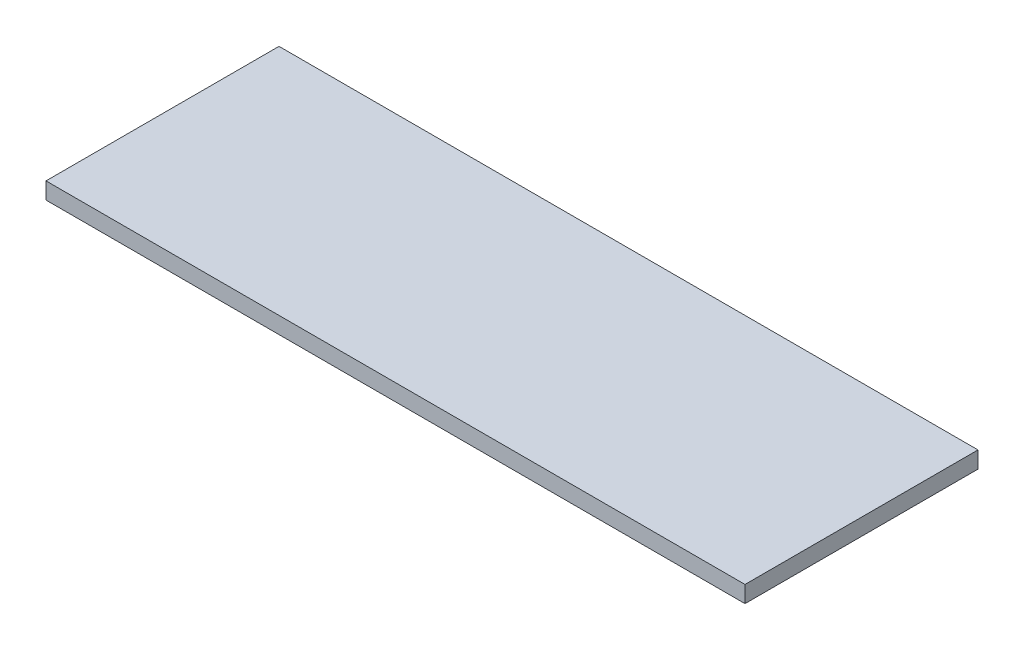
SolidWorks part; units mm, degrees
ref_plane "前视基准面" through (0, 0, 0) normal (0, 0, 1) x (1, 0, 0)
ref_plane "上视基准面" through (0, 0, 0) normal (0, 1, 0) x (1, 0, 0)
ref_plane "右视基准面" through (0, 0, 0) normal (1, 0, 0) x (0, 0, -1)
sketch "草图1" plane through (0, 0, 0) normal (0, 1, 0) x (1, 0, 0)
  line L1 (-21, 7) -> (21, 7)
  line L2 (-21, 7) -> (-21, -7)
  line L3 (-21, -7) -> (21, -7)
  line L4 (21, 7) -> (21, -7)
  line L5 (-21, 7) -> (21, -7) construction
  line L6 (-21, -7) -> (21, 7) construction
  point P0 (0, 0)
  dimension "D1" = 14
  dimension "D2" = 42
extrude "凸台-拉伸1" add sketch "草图1" along normal blind 1
